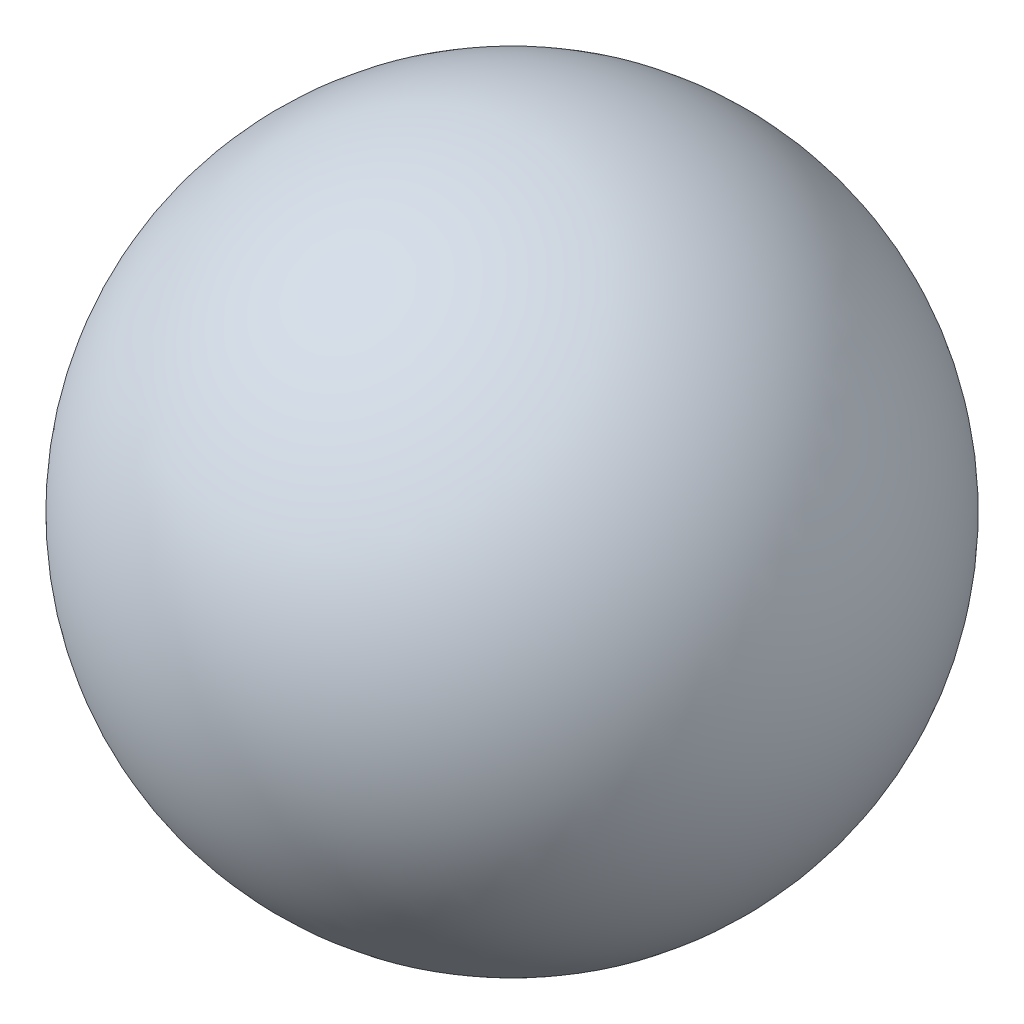
SolidWorks part; units mm, degrees
ref_plane "Front Plane" through (0, 0, 0) normal (0, 0, 1) x (1, 0, 0)
ref_plane "Top Plane" through (0, 0, 0) normal (0, 1, 0) x (1, 0, 0)
ref_plane "Right Plane" through (0, 0, 0) normal (1, 0, 0) x (0, 0, -1)
sketch "Sketch1" plane through (0, 0, 0) normal (0, 0, 1) x (1, 0, 0)
  line L0 (0, 11) -> (0, -11)
  arc A0 (0, 11) -> (0, -11) centre (0, 0) ccw
  dimension "D1" = 22
revolve "Revolve1" add sketch "Sketch1" angle 360 about L0
